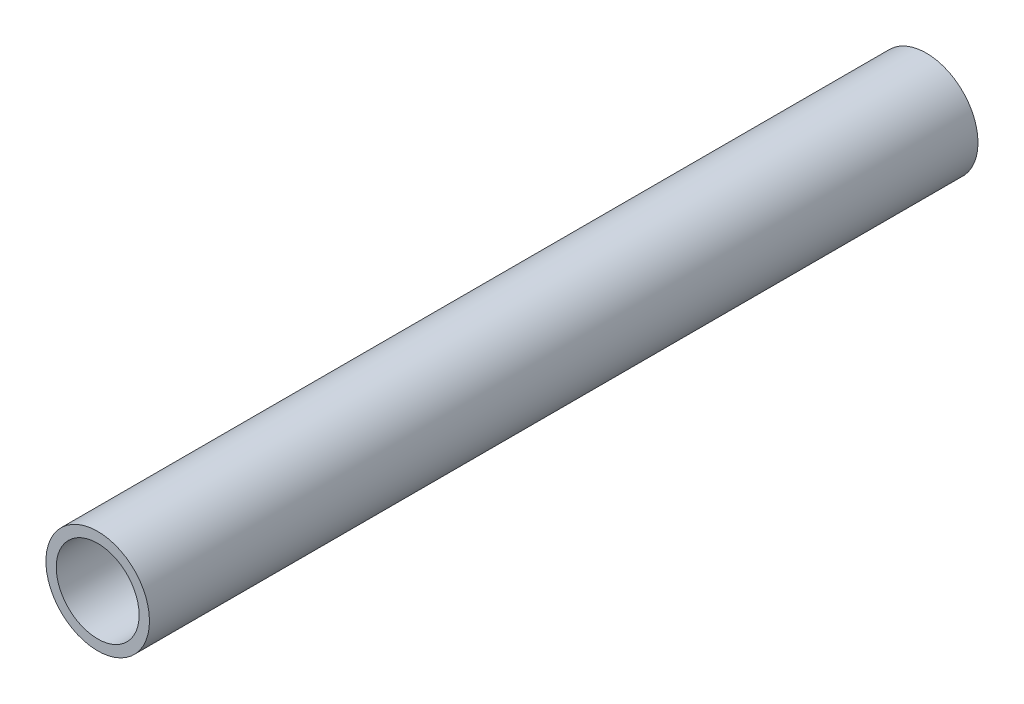
SolidWorks part; units mm, degrees
material "Thornel VCB-20 ｶｰﾎﾞﾝ ｸﾛｽ"
ref_plane "正面" through (0, 0, 0) normal (0, 0, 1) x (1, 0, 0)
ref_plane "平面" through (0, 0, 0) normal (0, 1, 0) x (1, 0, 0)
ref_plane "右側面" through (0, 0, 0) normal (1, 0, 0) x (0, 0, -1)
sketch "ｽｹｯﾁ1" plane through (0, 0, 0) normal (0, 0, 1) x (1, 0, 0)
  circle A0 centre (0, 0) radius 5
  circle A1 centre (0, 0) radius 4
  dimension "D1" = 10
  dimension "D2" = 8
extrude "ﾎﾞｽ - 押し出し1" add sketch "ｽｹｯﾁ1" along normal blind 80
sketch "ｽｹｯﾁ2" plane through (0, 0, 0) normal (0, 1, 0) x (1, 0, 0)
  line L0 (0, 0) -> (0, -80) construction
  line L1 (-4, -80) -> (4, -80) construction
